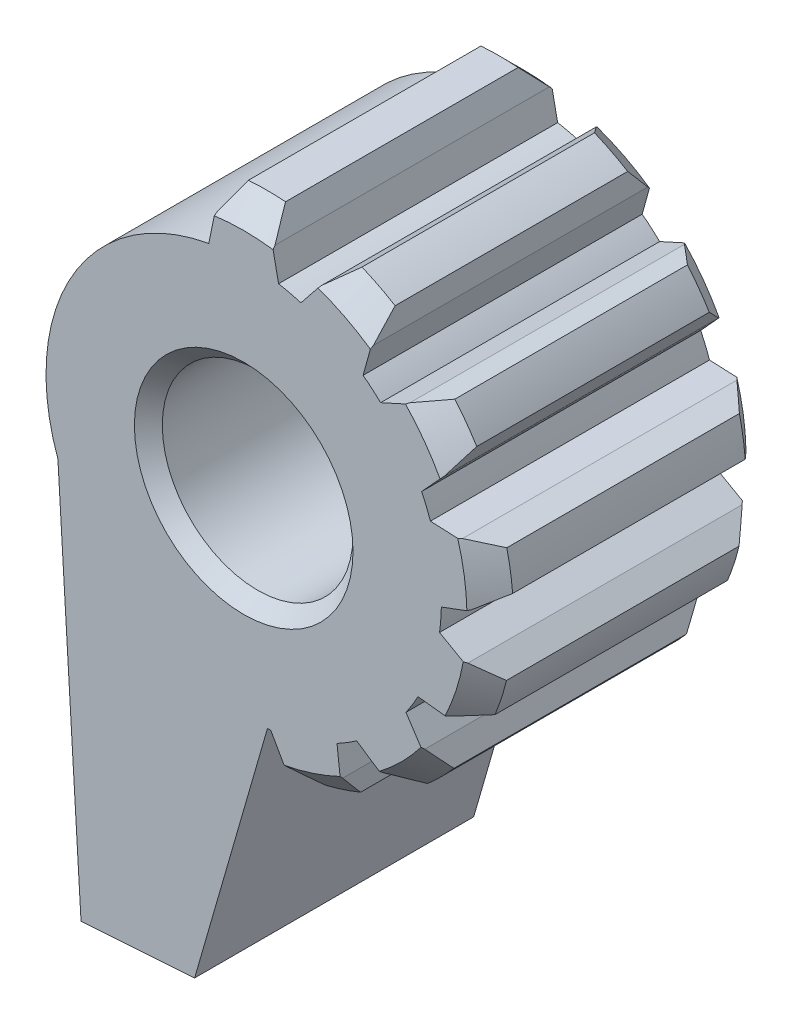
SolidWorks part; units mm, degrees
ref_plane "정면" through (0, 0, 0) normal (0, 0, 1) x (1, 0, 0)
ref_plane "윗면" through (0, 0, 0) normal (0, 1, 0) x (1, 0, 0)
ref_plane "우측면" through (0, 0, 0) normal (1, 0, 0) x (0, 0, -1)
sketch "스케치1" plane through (0, 0, 0) normal (0, 0, 1) x (1, 0, 0)
  line L0 (0, 0) -> (0, 5.3) construction
  line L1 (-0.4, 5.2849) -> (-0.6218, 4.811)
  line L2 (-0.6218, 4.811) -> (-0.75, 4.1833)
  line L3 (0.6218, 4.811) -> (0.75, 4.1833)
  line L4 (0.4, 5.2849) -> (0.6218, 4.811)
  circle A0 centre (0, 0) radius 4.25
  circle A1 centre (0, 0) radius 2.05
  arc A2 (0.4, 5.2849) -> (-0.4, 5.2849) centre (0, 0) ccw
  dimension "D1" = 4.1
  dimension "D2" = 8.5
  dimension "D5" = 5.3
  dimension "D3" = 0.8
  dimension "D4" = 1.5
extrude "보스-돌출1" add sketch "스케치1" along normal mid plane 6
pattern_circular "원형 패턴1" count 7 every 27 about axis through (0, 0, 0) along (0, 0, 1) of "보스-돌출1"
chamfer "모따기1" distance 0.5 angle 45 7 edges at (0, 5.3, -3) (1.6378, -5.0406, -3) (3.7477, -3.7477, -3) (5.0406, -1.6378, -3) (5.2347, 0.8291, -3) (4.2878, 3.1153, -3) (2.4061, 4.7223, -3)
chamfer "모따기2" distance 0.5 angle 45 7 edges at (0, 5.3, 3) (2.4061, 4.7223, 3) (4.2878, 3.1153, 3) (5.2347, 0.8291, 3) (5.0406, -1.6378, 3) (3.7477, -3.7477, 3) (1.6378, -5.0406, 3)
chamfer "모따기3" distance 0.3 angle 45 2 edges at (2.05, 0, 3) (2.05, 0, -3)
sketch "스케치4" plane through (0, 0, 0) normal (0, 0, 1) x (1, 0, 0)
  line L0 (-3.9943, -1.4519) -> (-3.4972, -9.8096)
  line L1 (-3.4972, -9.8096) -> (-1.0552, -9.6457)
  line L2 (-1.0552, -9.6457) -> (0.5102, -4.2193)
  line L3 (0.5102, -4.2193) -> (-3.9943, -1.4519)
  arc A0 (-0.75, 4.1833) -> (0.5794, -4.2103) centre (0, 0) ccw construction
  arc A1 (-0.75, 4.1833) -> (0.5794, -4.2103) centre (0, 0) ccw construction
extrude "보스-돌출2" add sketch "스케치4" along normal mid plane 6 contours L2 L3 L0 L1
